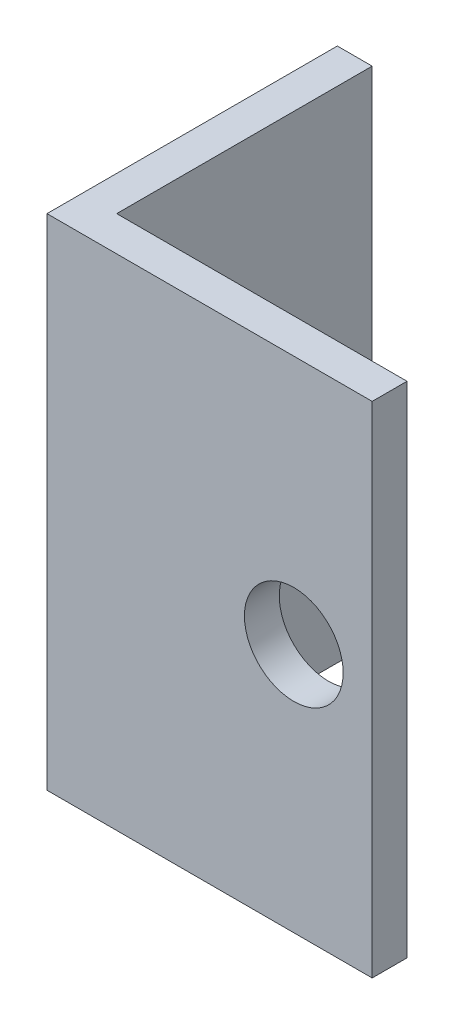
SolidWorks part; units mm, degrees
ref_plane "Alzado" through (0, 0, 0) normal (0, 0, 1) x (1, 0, 0)
ref_plane "Planta" through (0, 0, 0) normal (0, 1, 0) x (1, 0, 0)
ref_plane "Vista lateral" through (0, 0, 0) normal (1, 0, 0) x (0, 0, -1)
sketch "Croquis1" plane through (0, 0, 0) normal (0, 1, 0) x (1, 0, 0)
  line L0 (0, 0) -> (25, 0)
  line L1 (25, 0) -> (25, -3)
  line L2 (25, -3) -> (0, -3)
  line L3 (0, -3) -> (0, 0)
extrude "Saliente-Extruir1" add sketch "Croquis1" along normal blind 195
sketch "Croquis2" plane through (0, 0, 3) normal (0, 0, 1) x (1, 0, 0)
  line L0 (0, 195) -> (0, 0) construction
  line L1 (0, 0) -> (25, 0) construction
  line L2 (0, 195) -> (25, 195) construction
  circle A0 centre (18.25, 180) radius 4.25
  circle A1 centre (18.25, 97.5) radius 4.25
  circle A2 centre (18.25, 15) radius 4.25
  dimension "D1" = 18.25
  dimension "D2" = 15
  dimension "D3" = 97.5
  dimension "D4" = 15
extrude "Cortar-Extruir1" cut sketch "Croquis2" against normal blind 195
sketch "Croquis3" plane through (0, 195, 0) normal (0, 1, 0) x (1, 0, 0)
  line L1 (0, -3) -> (-4, -3)
  line L2 (0, -3) -> (0, 22)
  line L3 (0, 22) -> (-4, 22)
  line L4 (-4, -3) -> (-4, 22)
  dimension "D1" = 4
extrude "Saliente-Extruir2" add sketch "Croquis3" against normal blind 195
sketch "Croquis4" plane through (0, 0, 3) normal (0, 0, 1) x (1, 0, 0)
  line L1 (25, 195) -> (-4, 195)
  line L2 (25, 195) -> (25, 0)
  line L3 (25, 0) -> (-4, 0)
  line L4 (-4, 195) -> (-4, 0)
  circle A0 centre (18.25, 15) radius 4.25
  circle A1 centre (18.25, 97.5) radius 4.25
  circle A2 centre (18.25, 180) radius 4.25
extrude "Saliente-Extruir3" add sketch "Croquis4" along normal blind 1
sketch "Croquis5" plane through (0, 0, 4) normal (0, 0, 1) x (1, 0, 0)
  line L0 (25, 195) -> (-4, 195) construction
  line L1 (25, 0) -> (-124.8114, 0)
  line L2 (25, 0) -> (25, 152)
  line L3 (25, 152) -> (-124.8114, 152)
  line L4 (-124.8114, 0) -> (-124.8114, 152)
  dimension "D1" = 43
extrude "Cortar-Extruir4" cut sketch "Croquis5" against normal blind 40
sketch "Croquis6" plane through (0, 0, 4) normal (0, 0, 1) x (1, 0, 0)
  line L0 (25, 152) -> (25, 195) construction
  circle A0 centre (18.25, 173.5) radius 4.25
  point P4 (25, 173.5)
  dimension "D1" = 0
extrude "Cortar-Extruir5" cut sketch "Croquis6" against normal blind 40
sketch "Croquis7" plane through (0, 0, 4) normal (0, 0, 1) x (1, 0, 0)
  circle A0 centre (18.25, 180) radius 4.25
  circle A1 centre (18.25, 173.5) radius 4.25
  arc M5 (15.5114, 176.75) -> (20.9886, 176.75) centre (18.25, 180) cw
extrude "Saliente-Extruir4" add sketch "Croquis7" against normal blind 4 contours A1 M5
sketch "Croquis8" plane through (0, 195, 0) normal (0, 1, 0) x (1, 0, 0)
  line L0 (25, -4) -> (-4, -4) construction
  line L1 (-4, 22) -> (-3, 22)
  line L2 (-4, 22) -> (-4, -4)
  line L3 (-4, -4) -> (-3, -4)
  line L4 (-3, 22) -> (-3, -4)
  line L5 (0, 0) -> (0, 22) construction
  line L6 (25, -4) -> (25, 0) construction
  line L7 (-3, -4) -> (25, -4)
  line L10 (25, -4) -> (25, -3)
  line M5 (0, 22) -> (-4, 22)
  line M6 (-4, 22) -> (-4, -4)
  line M7 (-4, -4) -> (25, -4)
  dimension "D1" = 3
extrude "Cortar-Extruir6" cut sketch "Croquis8" against normal blind 60 contours L4 M5 M6 M7
sketch "Croquis9" plane through (0, 195, 0) normal (0, 1, 0) x (1, 0, 0)
  line L0 (25, -4) -> (25, 0) construction
  line L1 (-3, -4) -> (25, -4)
  line L2 (-3, -4) -> (-3, -3)
  line L3 (-3, -3) -> (25, -3)
  line L4 (25, -4) -> (25, -3)
  line L5 (25, 0) -> (0, 0) construction
  dimension "D1" = 3
extrude "Cortar-Extruir7" cut sketch "Croquis9" against normal blind 60
